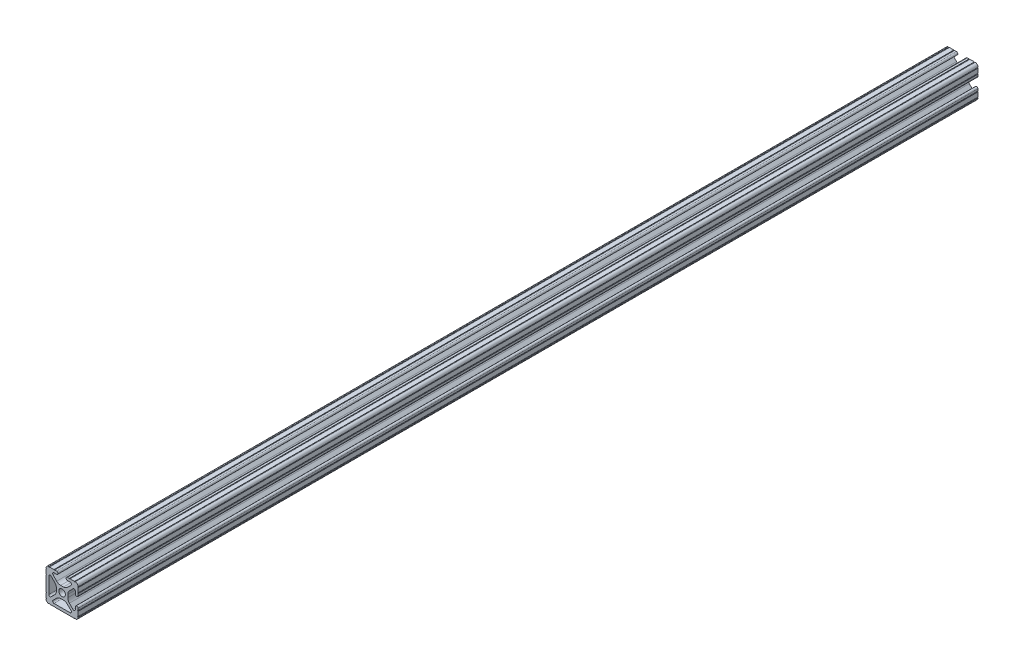
SolidWorks part; units mm, degrees
material "6061 Alloy"
ref_plane "Front Plane" through (0, 0, 0) normal (0, 0, 1) x (1, 0, 0)
ref_plane "Top Plane" through (0, 0, 0) normal (0, 1, 0) x (1, 0, 0)
ref_plane "Right Plane" through (0, 0, 0) normal (1, 0, 0) x (0, 0, -1)
sketch "Sketch1" plane through (0, 0, 0) normal (0, 0, 1) x (1, 0, 0)
  line L0 (0, 12.7) -> (-12.7, 12.7) construction
  line L1 (-4.5085, 0) -> (-4.5085, 2.9459)
  line L2 (-6.0545, 12.7) -> (-10.1745, 12.7) construction
  line L3 (-11.6284, 12.3843) -> (-4.3434, 12.3843) construction
  line L4 (-6.3702, 10.4902) -> (-6.3702, 12.7) construction
  line L6 (-2.9459, 4.5085) -> (0, 4.5085)
  line L7 (0, 0) -> (0, 12.7) construction
  line L8 (0, 0) -> (-12.7, 0) construction
  line L9 (0.7813, 0.7813) -> (-0.7813, -0.7813) construction
  line L10 (-2.9459, 4.5085) -> (-7.1192, 8.6818)
  line L11 (-4.5085, 2.9459) -> (-8.6818, 7.1192)
  line L13 (0, 0) -> (-12.7, 12.7) construction
  line L14 (-10.4902, 12.7) -> (-4.3434, 12.7)
  line L15 (-4.3434, 12.7) -> (-4.3434, 10.4902) construction
  line L16 (-4.3434, 10.4902) -> (-6.3702, 10.4902)
  line L17 (-12.7, 10.4902) -> (-12.7, 4.3434)
  line L18 (-10.4902, 4.3434) -> (-10.4902, 6.3702)
  circle A0 centre (0, 0) radius 2.6035
  arc A1 (-4.3434, 10.4902) -> (-4.3434, 12.7) centre (-4.3434, 11.5951) ccw
  arc A2 (-7.1192, 8.6818) -> (-6.3702, 10.4902) centre (-6.3702, 9.4309) cw
  arc A3 (-8.6818, 7.1192) -> (-10.4902, 6.3702) centre (-9.4309, 6.3702) ccw
  arc A4 (-10.4902, 4.3434) -> (-12.7, 4.3434) centre (-11.5951, 4.3434) cw
  arc A5 (-10.4902, 12.7) -> (-12.7, 10.4902) centre (-10.4902, 10.4902) ccw
  arc A6 (-10.4902, 12.7) -> (-9.8588, 12.7) centre (-10.1745, 12.7) ccw
  arc A7 (-6.3702, 12.7) -> (-5.7388, 12.7) centre (-6.0545, 12.7) ccw
  arc A8 (-12.7, 6.3702) -> (-12.7, 5.7388) centre (-12.7, 6.0545) cw
  arc A9 (-12.7, 10.4902) -> (-12.7, 9.8588) centre (-12.7, 10.1745) cw
  dimension "D1" = 5.207
  dimension "D5" = 14.859
  dimension "D9" = 0
  dimension "D2" = 25.4
  dimension "D12" = 0.6314
  dimension "D10" = 2.2098
  dimension "D3" = 9.017
  dimension "D4" = 9.017
  dimension "D6" = 25.4
  dimension "D7" = 6.477
  dimension "D8" = 2.2098
  dimension "D11" = 12.7
sketch "Sketch3" plane through (0, 0, 0) normal (0, 0, 1) x (1, 0, 0)
  line L0 (-2.9459, 4.5085) -> (0, 4.5085) construction
  line L1 (-2.9459, 4.5085) -> (-7.1192, 8.6818) construction
  line L2 (-4.3434, 10.4902) -> (-6.3702, 10.4902) construction
  line L3 (-10.4902, 12.7) -> (-4.3434, 12.7) construction
  line L4 (-4.5085, 0) -> (-4.5085, 2.9459) construction
  line L5 (-4.5085, 2.9459) -> (-8.6818, 7.1192) construction
  line L6 (-10.4902, 4.3434) -> (-10.4902, 6.3702) construction
  line L7 (-12.7, 10.4902) -> (-12.7, 4.3434) construction
  line L8 (-1.1153, 4.5085) -> (1.1153, 4.5085)
  line L9 (-4.2404, 5.803) -> (-7.1192, 8.6818)
  line L10 (-4.3434, 10.4902) -> (-6.3702, 10.4902)
  line L11 (-9.8588, 12.7) -> (-6.3702, 12.7)
  line L12 (-4.5085, -1.1153) -> (-4.5085, 1.1153)
  line L13 (-5.803, 4.2404) -> (-8.6818, 7.1192)
  line L14 (-10.4902, 0) -> (-10.4902, 6.3702)
  line L15 (-12.7, 9.8588) -> (-12.7, 6.3702)
  line L16 (-5.7388, 12.7) -> (-4.3434, 12.7)
  line L17 (-12.7, 5.7388) -> (-12.7, 0)
  line L18 (0, 0) -> (0, 12.7) construction
  line L19 (0, 0) -> (-12.7, 0) construction
  line L20 (12.7, 5.7388) -> (12.7, 4.3434)
  line L21 (5.7388, 12.7) -> (4.3434, 12.7)
  line L22 (12.7, 9.8588) -> (12.7, 6.3702)
  line L23 (10.4902, 4.3434) -> (10.4902, 6.3702)
  line L24 (5.803, 4.2404) -> (8.6818, 7.1192)
  line L25 (4.5085, -1.1153) -> (4.5085, 1.1153)
  line L26 (9.8588, 12.7) -> (6.3702, 12.7)
  line L27 (4.3434, 10.4902) -> (6.3702, 10.4902)
  line L28 (4.2404, 5.803) -> (7.1192, 8.6818)
  line L29 (4.2404, -5.803) -> (7.1192, -8.6818)
  line L30 (4.3434, -10.4902) -> (6.3702, -10.4902)
  line L31 (9.8588, -12.7) -> (6.3702, -12.7)
  line L32 (5.803, -4.2404) -> (8.6818, -7.1192)
  line L33 (10.4902, -4.3434) -> (10.4902, -6.3702)
  line L34 (12.7, -9.8588) -> (12.7, -6.3702)
  line L35 (5.7388, -12.7) -> (4.3434, -12.7)
  line L36 (12.7, -5.7388) -> (12.7, -4.3434)
  line L37 (-12.7, -5.7388) -> (-12.7, 0)
  line L38 (-5.7388, -12.7) -> (4.3434, -12.7)
  line L39 (-12.7, -9.8588) -> (-12.7, -6.3702)
  line L40 (-10.4902, 0) -> (-10.4902, -6.3702)
  line L41 (-5.803, -4.2404) -> (-8.6818, -7.1192)
  line L42 (-9.8588, -12.7) -> (-6.3702, -12.7)
  line L43 (4.3434, -10.4902) -> (-6.3702, -10.4902)
  line L44 (-4.2404, -5.803) -> (-7.1192, -8.6818)
  line L45 (-1.1153, -4.5085) -> (1.1153, -4.5085)
  arc A0 (-10.4902, 12.7) -> (-9.8588, 12.7) centre (-10.1745, 12.7) ccw construction
  arc A1 (-6.3702, 10.4902) -> (-7.1192, 8.6818) centre (-6.3702, 9.4309) ccw construction
  arc A2 (-4.3434, 10.4902) -> (-4.3434, 12.7) centre (-4.3434, 11.5951) ccw construction
  arc A3 (-8.6818, 7.1192) -> (-10.4902, 6.3702) centre (-9.4309, 6.3702) ccw construction
  arc A4 (-12.7, 4.3434) -> (-10.4902, 4.3434) centre (-11.5951, 4.3434) ccw construction
  arc A5 (-6.3702, 12.7) -> (-5.7388, 12.7) centre (-6.0545, 12.7) ccw construction
  arc A6 (-10.4902, 12.7) -> (-12.7, 10.4902) centre (-10.4902, 10.4902) ccw construction
  arc A7 (-12.7, 9.8588) -> (-12.7, 10.4902) centre (-12.7, 10.1745) ccw construction
  arc A8 (-12.7, 5.7388) -> (-12.7, 6.3702) centre (-12.7, 6.0545) ccw construction
  arc A9 (-10.4902, 12.7) -> (-9.8588, 12.7) centre (-10.1745, 12.7) ccw
  arc A10 (-6.3702, 10.4902) -> (-7.1192, 8.6818) centre (-6.3702, 9.4309) ccw
  arc A11 (-4.3434, 10.4902) -> (-4.3434, 12.7) centre (-4.3434, 11.5951) ccw
  arc A12 (-8.6818, 7.1192) -> (-10.4902, 6.3702) centre (-9.4309, 6.3702) ccw
  arc A14 (-6.3702, 12.7) -> (-5.7388, 12.7) centre (-6.0545, 12.7) ccw
  arc A15 (-10.4902, 12.7) -> (-12.7, 10.4902) centre (-10.4902, 10.4902) ccw
  arc A16 (-12.7, 9.8588) -> (-12.7, 10.4902) centre (-12.7, 10.1745) ccw
  arc A17 (-12.7, 5.7388) -> (-12.7, 6.3702) centre (-12.7, 6.0545) ccw
  arc A18 (-1.1153, 4.5085) -> (-4.2404, 5.803) centre (-1.1153, 8.9281) cw
  arc A19 (4.5085, 1.1153) -> (5.803, 4.2404) centre (8.9281, 1.1153) cw
  arc A20 (1.1153, 4.5085) -> (4.2404, 5.803) centre (1.1153, 8.9281) ccw
  arc A21 (-4.5085, 1.1153) -> (-5.803, 4.2404) centre (-8.9281, 1.1153) ccw
  arc A22 (12.7, 5.7388) -> (12.7, 6.3702) centre (12.7, 6.0545) cw
  arc A23 (12.7, 9.8588) -> (12.7, 10.4902) centre (12.7, 10.1745) cw
  arc A24 (10.4902, 12.7) -> (12.7, 10.4902) centre (10.4902, 10.4902) cw
  arc A25 (6.3702, 12.7) -> (5.7388, 12.7) centre (6.0545, 12.7) cw
  arc A26 (12.7, 4.3434) -> (10.4902, 4.3434) centre (11.5951, 4.3434) cw
  arc A27 (8.6818, 7.1192) -> (10.4902, 6.3702) centre (9.4309, 6.3702) cw
  arc A28 (4.3434, 10.4902) -> (4.3434, 12.7) centre (4.3434, 11.5951) cw
  arc A29 (6.3702, 10.4902) -> (7.1192, 8.6818) centre (6.3702, 9.4309) cw
  arc A30 (10.4902, 12.7) -> (9.8588, 12.7) centre (10.1745, 12.7) cw
  arc A31 (10.4902, -12.7) -> (9.8588, -12.7) centre (10.1745, -12.7) ccw
  arc A32 (6.3702, -10.4902) -> (7.1192, -8.6818) centre (6.3702, -9.4309) ccw
  arc A34 (8.6818, -7.1192) -> (10.4902, -6.3702) centre (9.4309, -6.3702) ccw
  arc A35 (12.7, -4.3434) -> (10.4902, -4.3434) centre (11.5951, -4.3434) ccw
  arc A36 (6.3702, -12.7) -> (5.7388, -12.7) centre (6.0545, -12.7) ccw
  arc A37 (10.4902, -12.7) -> (12.7, -10.4902) centre (10.4902, -10.4902) ccw
  arc A38 (12.7, -9.8588) -> (12.7, -10.4902) centre (12.7, -10.1745) ccw
  arc A39 (12.7, -5.7388) -> (12.7, -6.3702) centre (12.7, -6.0545) ccw
  arc A40 (-4.5085, -1.1153) -> (-5.803, -4.2404) centre (-8.9281, -1.1153) cw
  arc A41 (1.1153, -4.5085) -> (4.2404, -5.803) centre (1.1153, -8.9281) cw
  arc A42 (4.5085, -1.1153) -> (5.803, -4.2404) centre (8.9281, -1.1153) ccw
  arc A43 (-1.1153, -4.5085) -> (-4.2404, -5.803) centre (-1.1153, -8.9281) ccw
  arc A44 (-12.7, -5.7388) -> (-12.7, -6.3702) centre (-12.7, -6.0545) cw
  arc A45 (-12.7, -9.8588) -> (-12.7, -10.4902) centre (-12.7, -10.1745) cw
  arc A46 (-10.4902, -12.7) -> (-12.7, -10.4902) centre (-10.4902, -10.4902) cw
  arc A47 (-6.3702, -12.7) -> (-5.7388, -12.7) centre (-6.0545, -12.7) cw
  arc A49 (-8.6818, -7.1192) -> (-10.4902, -6.3702) centre (-9.4309, -6.3702) cw
  arc A51 (-6.3702, -10.4902) -> (-7.1192, -8.6818) centre (-6.3702, -9.4309) cw
  arc A52 (-10.4902, -12.7) -> (-9.8588, -12.7) centre (-10.1745, -12.7) cw
  circle A53 centre (0, 0) radius 2.6035 construction
  circle A54 centre (0, 0) radius 2.6035
  point P135 (4.5085, 0)
  dimension "D2" = 4.4196
extrude "Extrude1" add sketch "Sketch3" along normal mid plane 711.2
equation "\"D10@Sketch1\" = \"D8@Sketch1\""
equation "\"D11@Sketch1\" = \"D6@Sketch1\"/2"
equation "\"D12@Sketch1\" = \"D8@Sketch1\"/3.5"
equation "\"D2@Sketch3\" = \"D8@Sketch1\"*2"
